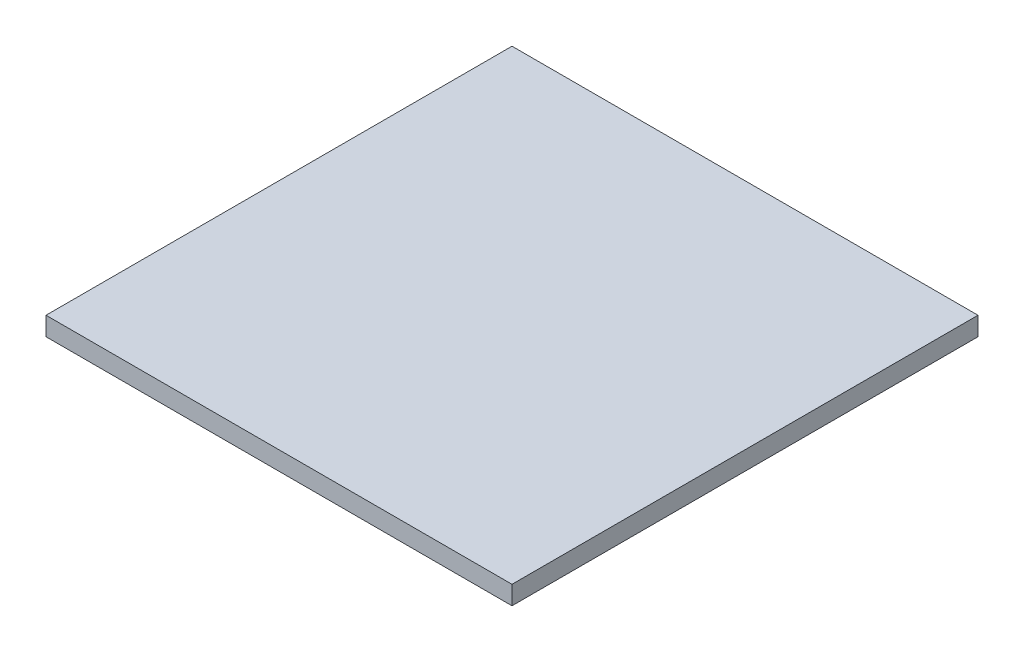
SolidWorks part; units mm, degrees
ref_plane "Front Plane" through (0, 0, 0) normal (0, 0, 1) x (1, 0, 0)
ref_plane "Top Plane" through (0, 0, 0) normal (0, 1, 0) x (1, 0, 0)
ref_plane "Right Plane" through (0, 0, 0) normal (1, 0, 0) x (0, 0, -1)
sketch "Sketch8" plane through (0, 0, 0) normal (0, 1, 0) x (1, 0, 0)
  line L1 (0, 0) -> (150, 0)
  line L2 (0, 0) -> (0, 150)
  line L3 (0, 150) -> (150, 150)
  line L4 (150, 0) -> (150, 150)
  dimension "D1" = 150
extrude "Boss-Extrude2" add sketch "Sketch8" along normal blind 6
sketch "Sketch10" plane through (0, 6, 0) normal (0, 1, 0) x (1, 0, 0)
  line L0 (0, 150) -> (150, 0) construction
  line L3 (0, 0) -> (150, 150) construction
